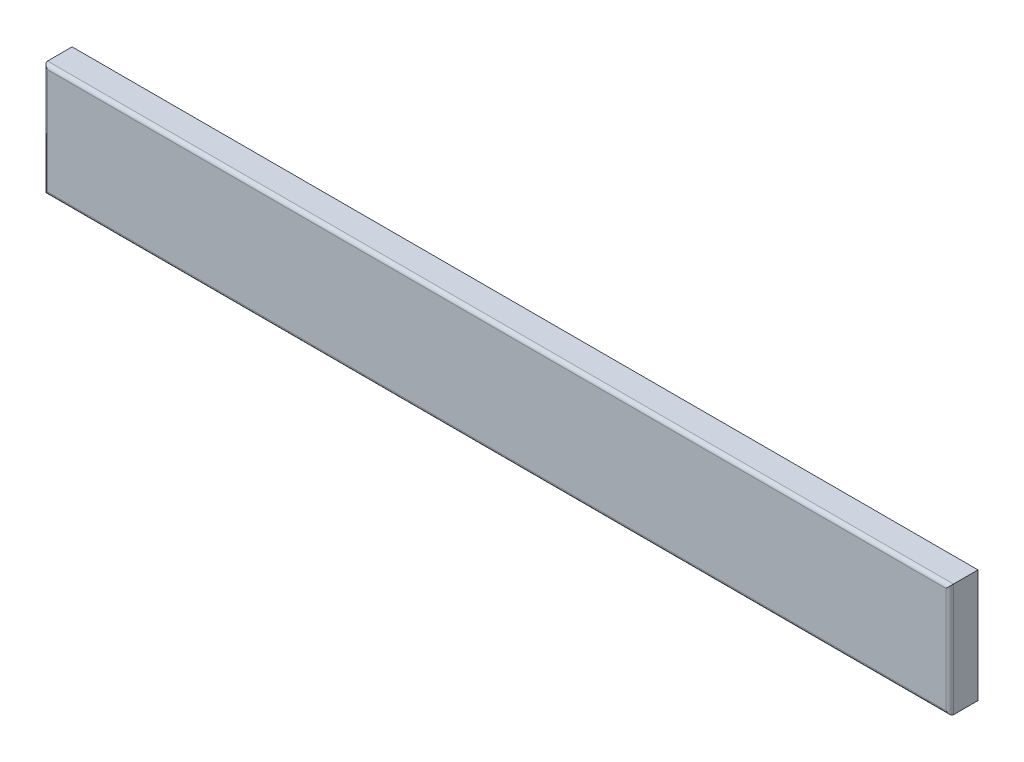
SolidWorks part; units mm, degrees
ref_plane "Front Plane" through (0, 0, 0) normal (0, 0, 1) x (1, 0, 0)
ref_plane "Top Plane" through (0, 0, 0) normal (0, 1, 0) x (1, 0, 0)
ref_plane "Right Plane" through (0, 0, 0) normal (1, 0, 0) x (0, 0, -1)
sketch "Sketch1" plane through (0, 0, 0) normal (0, 0, 1) x (1, 0, 0)
  line L1 (-304.8, -38.1) -> (304.8, -38.1)
  line L2 (-304.8, -38.1) -> (-304.8, 38.1)
  line L3 (-304.8, 38.1) -> (304.8, 38.1)
  line L4 (304.8, -38.1) -> (304.8, 38.1)
  line L5 (-304.8, -38.1) -> (304.8, 38.1) construction
  line L6 (-304.8, 38.1) -> (304.8, -38.1) construction
  point P0 (0, 0)
  dimension "D1" = 76.2
  dimension "D2" = 609.6
extrude "Boss-Extrude1" add sketch "Sketch1" along normal blind 2.54
sketch "Sketch2" plane through (0, 0, 2.54) normal (0, 0, 1) x (1, 0, 0)
  line L0 (302.26, 35.56) -> (-302.26, 35.56)
  line L1 (-302.26, 35.56) -> (-302.26, -35.56)
  line L2 (-302.26, -35.56) -> (302.26, -35.56)
  line L3 (302.26, -35.56) -> (302.26, 35.56)
  line L4 (304.8, -38.1) -> (304.8, 38.1)
  line L5 (304.8, 38.1) -> (-304.8, 38.1)
  line L6 (-304.8, 38.1) -> (-304.8, -38.1)
  line L7 (-304.8, -38.1) -> (304.8, -38.1)
  line L8 (304.8, -38.1) -> (304.8, 38.1)
  line L9 (304.8, 38.1) -> (-304.8, 38.1)
  line L10 (-304.8, 38.1) -> (-304.8, -38.1)
  line L11 (-304.8, -38.1) -> (304.8, -38.1)
  dimension "D1" = 0
  dimension "D2" = 2.54
extrude "Boss-Extrude2" add sketch "Sketch2" against normal blind 19.05
fillet "Fillet1" radius 2.54 4 edges at (0, -38.1, 2.54) (-304.8, 0, 2.54) (0, 38.1, 2.54) (304.8, 0, 2.54)
